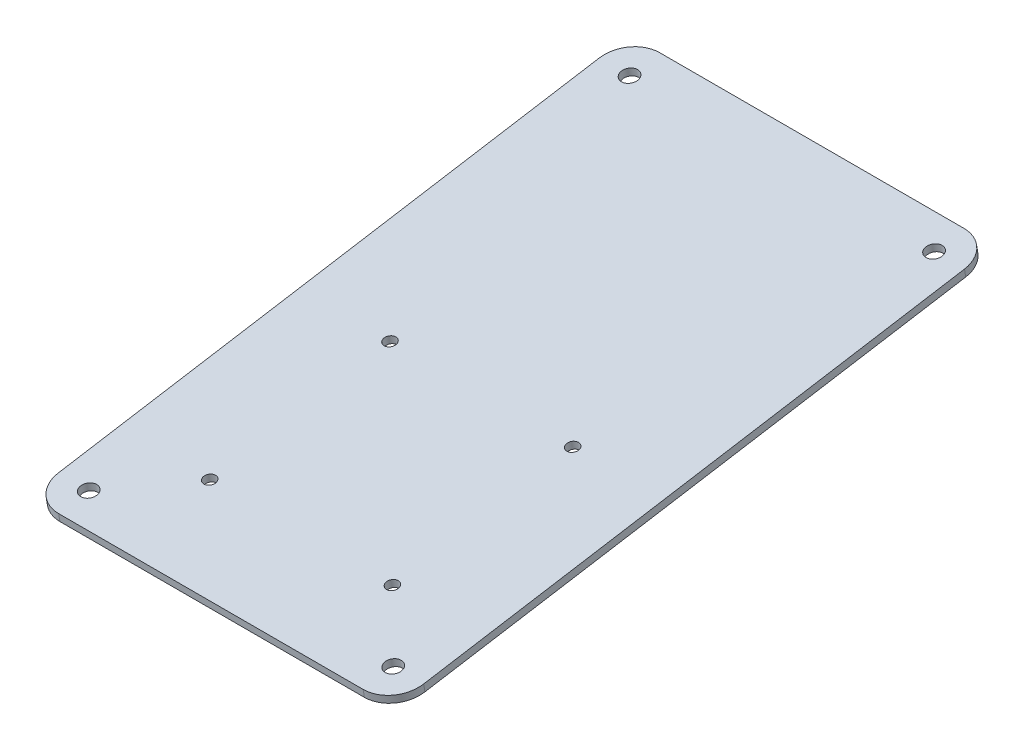
SolidWorks part; units mm, degrees
material "6061-T6 (SS)"
ref_plane "Front Plane" through (0, 0, 0) normal (0, 0, 1) x (1, 0, 0)
ref_plane "Top Plane" through (0, 0, 0) normal (0, 1, 0) x (1, 0, 0)
ref_plane "Right Plane" through (0, 0, 0) normal (1, 0, 0) x (0, 0, -1)
sketch "Sketch1" plane through (0, 687.5237, 112.9928) normal (0, 0.9868, 0.1622) x (1, 0, 0)
  line L0 (-76.2, -1180.4792) -> (-76.2, -926.4792) construction
  line L1 (-76.2, -926.4792) -> (76.2, -926.4792) construction
  line L2 (76.2, -1180.4792) -> (76.2, -926.4792) construction
  line L3 (-76.2, -1180.4792) -> (76.2, -1180.4792) construction
  line L4 (-76.2, -1167.7792) -> (-76.2, -939.1792)
  line L5 (-63.5, -926.4792) -> (63.5, -926.4792)
  line L6 (76.2, -1167.7792) -> (76.2, -939.1792)
  line L7 (-63.5, -1180.4792) -> (63.5, -1180.4792)
  arc A0 (63.5, -926.4792) -> (76.2, -939.1792) centre (63.5, -939.1792) cw
  arc A1 (-76.2, -939.1792) -> (-63.5, -926.4792) centre (-63.5, -939.1792) cw
  arc A2 (76.2, -1167.7792) -> (63.5, -1180.4792) centre (63.5, -1167.7792) cw
  arc A3 (-76.2, -1167.7792) -> (-63.5, -1180.4792) centre (-63.5, -1167.7792) ccw
  circle A4 centre (63.5, -1167.7792) radius 12.7 construction
extrude "Boss-Extrude1" add sketch "Sketch1" along normal up to vertex (3.175 mm away) from vertex at 0
hole_wizard "1/4 Clearance Hole1" positions "Sketch2" profile "Sketch3" hole size "1/4" standard "ANSI Inch" end condition through all
sketch "Sketch2" plane through (0, 690.6566, 113.5077) normal (0, 0.9868, 0.1622) x (1, 0, 0)
  point P0 (-63.5, -1167.7792)
  point P3 (63.5, -1167.7792)
  point P6 (63.5, -939.1792)
  point P9 (-63.5, -939.1792)
sketch "Sketch3" plane through (-63.5, 501.2756, 1265.8285) normal (1, 0, 0) x (0, -0.1622, 0.9868)
  line L0 (0, 0) -> (0, 43.8214)
  line L1 (0, 43.8214) -> (3.3782, 43.8214)
  line L2 (3.3782, 43.8214) -> (3.3782, 0)
  line L5 (3.3782, 0) -> (0, 0)
  line L11 (0, -6.35) -> (0, 107.95) construction
  dimension "Thru Hole Dia." = 6.7564
  dimension "Thru Hole Depth" = 43.8214
hole_wizard "#10 (0.1935) Diameter Hole1" positions "Sketch4" profile "Sketch5" hole size "#10" standard "ANSI Inch" end condition through all
sketch "Sketch4" plane through (0, 690.6566, 113.5077) normal (0, 0.9868, 0.1622) x (1, 0, 0)
  point P0 (38.1, -1142.3792)
  point P3 (-38.1, -1142.3792)
  point P6 (38.1, -1066.1792)
  point P9 (-38.1, -1066.1792)
sketch "Sketch5" plane through (38.1, 505.3948, 1240.7647) normal (1, 0, 0) x (0, -0.1622, 0.9868)
  line L0 (0, 0) -> (0, 43.8214)
  line L1 (0, 43.8214) -> (2.4574, 43.8214)
  line L2 (2.4574, 43.8214) -> (2.4574, 0)
  line L5 (2.4574, 0) -> (0, 0)
  line L11 (0, -6.35) -> (0, 107.95) construction
  dimension "Thru Hole Dia." = 4.9149
  dimension "Thru Hole Depth" = 43.8214
